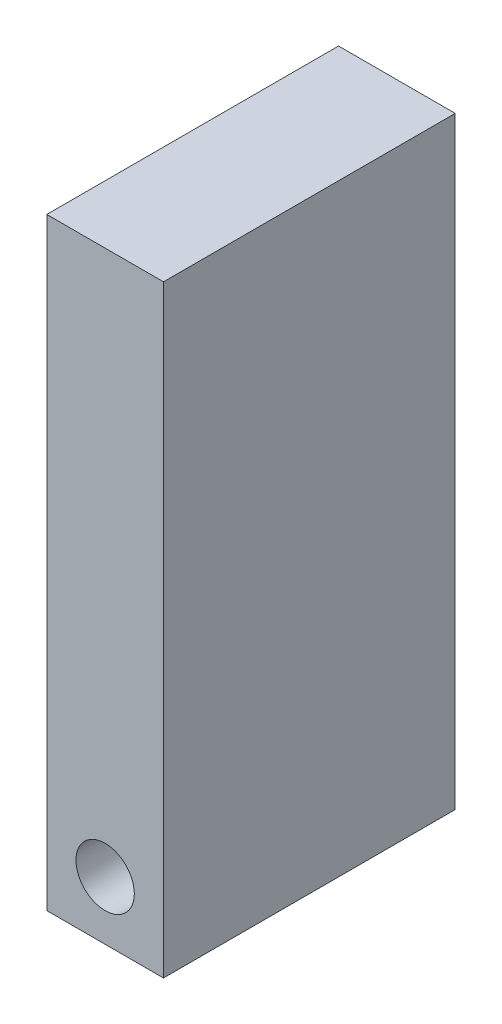
SolidWorks part; units mm, degrees
ref_plane "前视基准面" through (0, 0, 0) normal (0, 0, 1) x (1, 0, 0)
ref_plane "上视基准面" through (0, 0, 0) normal (0, 1, 0) x (1, 0, 0)
ref_plane "右视基准面" through (0, 0, 0) normal (1, 0, 0) x (0, 0, -1)
sketch "草图1" plane through (0, 0, 0) normal (0, 0, 1) x (1, 0, 0)
  line L0 (0, 0) -> (6, 0)
  line L1 (6, 0) -> (6, -28)
  line L2 (6, -28) -> (0, -28)
  line L3 (0, -28) -> (0, 0)
  circle A0 centre (3, -25) radius 1.5
  dimension "D5" = 3
  dimension "D1" = 6
  dimension "D2" = 28
  dimension "D3" = 3
  dimension "D4" = 25
extrude "凸台-拉伸1" add sketch "草图1" along normal blind 20
sketch "草图2" plane through (0, 0, 0) normal (0, 1, 0) x (1, 0, 0)
  line L0 (6, -20) -> (0, -20) construction
  line L1 (6, -20) -> (6, 0) construction
  line L2 (6, 0) -> (0, 0) construction
  line L3 (0, -20) -> (0, 0) construction
  line L4 (6, -20) -> (0, -20)
  line L5 (6, -20) -> (6, 0)
  line L6 (6, 0) -> (0, 0)
  line L7 (0, -20) -> (0, 0)
extrude "凸台-拉伸2" add sketch "草图2" along normal blind 3
sketch "草图3" plane through (6, 0, 0) normal (1, 0, 0) x (0, 0, -1)
  line L0 (0, 3) -> (0, -28)
  line L1 (0, -28) -> (-5, -28)
  line L2 (-20, -28) -> (0, -28) construction
  line L3 (-5, -28) -> (-5, 3)
  line L4 (-20, 3) -> (0, 3) construction
  line L5 (-5, 3) -> (0, 3)
  dimension "D1" = 5
extrude "切除-拉伸1" cut sketch "草图3" against normal blind 8
